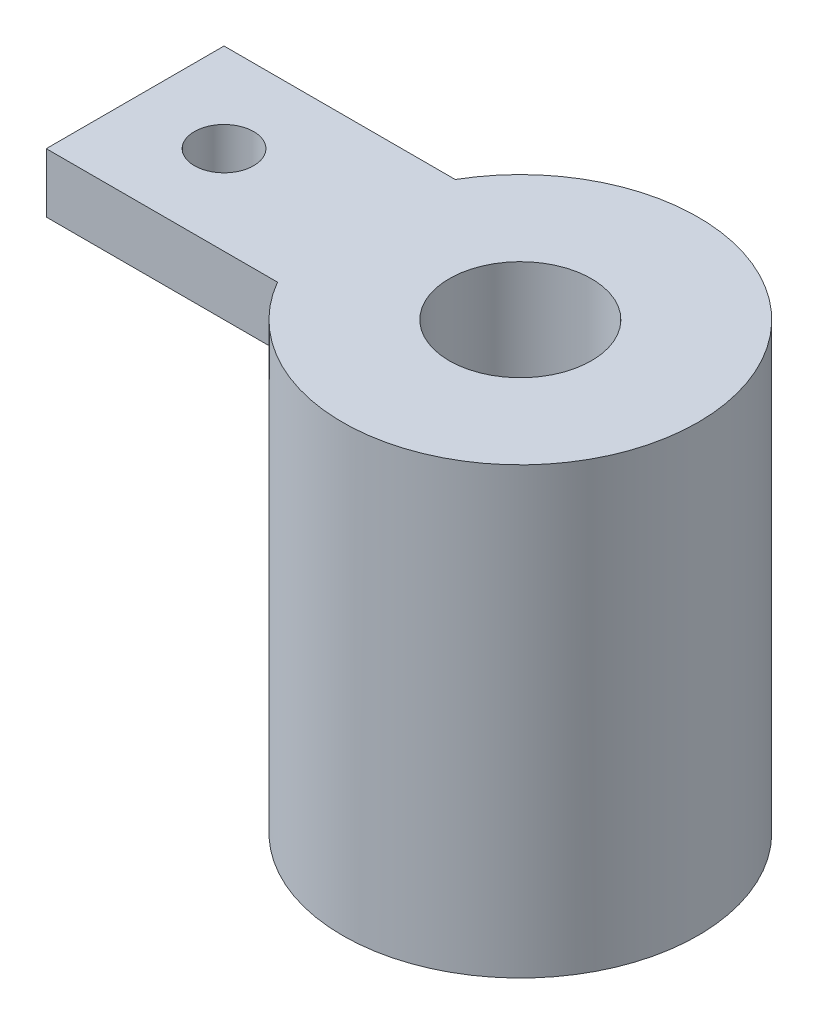
SolidWorks part; units mm, degrees
ref_plane "Front Plane" through (0, 0, 0) normal (0, 0, 1) x (1, 0, 0)
ref_plane "Top Plane" through (0, 0, 0) normal (0, 1, 0) x (1, 0, 0)
ref_plane "Right Plane" through (0, 0, 0) normal (1, 0, 0) x (0, 0, -1)
sketch "Sketch1" plane through (0, 0, 0) normal (0, 1, 0) x (1, 0, 0)
  circle A0 centre (0, 0) radius 9.525
  circle A1 centre (0, 0) radius 15.24
  dimension "D1" = 19.05
  dimension "D2" = 30.48
extrude "Boss-Extrude2" add sketch "Sketch1" along normal blind 12.7
sketch "Sketch3" plane through (0, 12.7, 0) normal (0, 1, 0) x (1, 0, 0)
  circle A0 centre (0, 0) radius 15.24
extrude "Boss-Extrude3" add sketch "Sketch3" along normal blind 12.7
sketch "Sketch4" plane through (0, 25.4, 0) normal (0, 1, 0) x (1, 0, 0)
  circle A0 centre (0, 0) radius 6.096
  circle A1 centre (0, 0) radius 15.24
  dimension "D1" = 12.192
extrude "Boss-Extrude4" add sketch "Sketch4" along normal blind 12.7
sketch "Sketch5" plane through (0, 12.7, 0) normal (0, -1, 0) x (1, 0, 0)
  line L1 (-1.016, 6.35) -> (1.016, 6.35)
  line L2 (-1.016, 6.35) -> (-1.016, -6.35)
  line L3 (-1.016, -6.35) -> (1.016, -6.35)
  line L4 (1.016, 6.35) -> (1.016, -6.35)
  dimension "D1" = 1.016
  dimension "D2" = 1.016
  dimension "D3" = 6.35
  dimension "D4" = 6.35
extrude "Boss-Extrude5" add sketch "Sketch5" along normal blind 12.7
sketch "Sketch6" plane through (0, 38.1, 0) normal (0, 1, 0) x (1, 0, 0)
  line L0 (-13.1982, 7.62) -> (-33.02, 7.62)
  line L1 (-33.02, 7.62) -> (-33.02, -7.62)
  line L2 (-33.02, -7.62) -> (-13.1982, -7.62)
  circle A0 centre (0, 0) radius 15.24 construction
  arc A1 (-13.1982, 7.62) -> (-13.1982, -7.62) centre (0, 0) ccw
  dimension "D3" = 33.02
  dimension "D1" = 7.62
  dimension "D2" = 7.62
extrude "Boss-Extrude6" add sketch "Sketch6" against normal blind 5.08
sketch "Sketch7" plane through (0, 38.1, 0) normal (0, 1, 0) x (1, 0, 0)
  line L0 (-33.02, 7.62) -> (-33.02, -7.62) construction
  line L2 (-13.1982, 7.62) -> (-33.02, 7.62) construction
  circle A0 centre (-25.4, 0) radius 2.54
  point P6 (-26.8996, 7.62)
  dimension "D3" = 5.08
  dimension "D1" = 7.62
  dimension "D2" = 7.62
extrude "Cut-Extrude1" cut sketch "Sketch7" against normal blind 5.08
